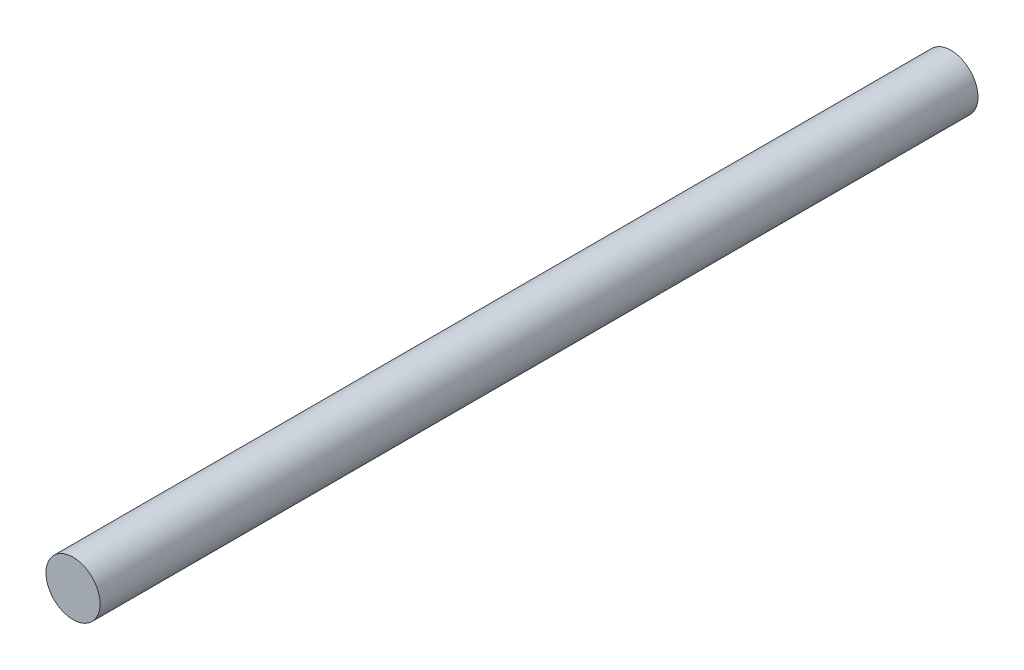
SolidWorks part; units mm, degrees
material "СТ3КП"
ref_plane "Спереди" through (0, 0, 0) normal (0, 0, 1) x (1, 0, 0)
ref_plane "Сверху" through (0, 0, 0) normal (0, 1, 0) x (1, 0, 0)
ref_plane "Справа" through (0, 0, 0) normal (1, 0, 0) x (0, 0, -1)
sketch "Эскиз1" plane through (0, 0, 0) normal (0, 0, 1) x (1, 0, 0)
  circle A0 centre (0, 0) radius 6 construction
  circle A1 centre (0, 0) radius 6
extrude "Бобышка-Вытянуть1" add sketch "Эскиз1" along normal up to surface (97.3 mm away)
mirror "Зеркальное отражение1" about plane through (0, 0, 0) normal (0, 0, 1) of bodies 103
